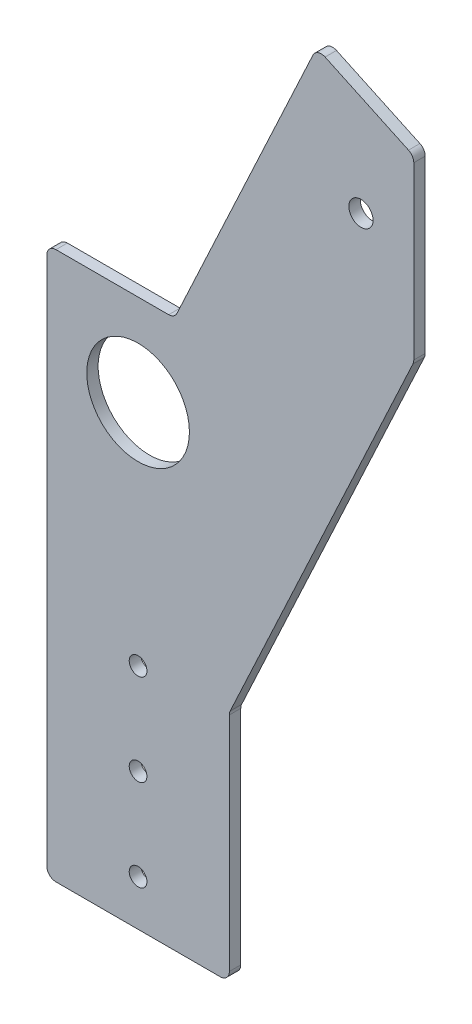
SolidWorks part; units mm, degrees
ref_plane "Front Plane" through (0, 0, 0) normal (0, 0, 1) x (1, 0, 0)
ref_plane "Top Plane" through (0, 0, 0) normal (0, 1, 0) x (1, 0, 0)
ref_plane "Right Plane" through (0, 0, 0) normal (1, 0, 0) x (0, 0, -1)
sketch "Sketch1" plane through (0, 0, 0) normal (0, 0, 1) x (1, 0, 0)
  line L0 (10.1326, 114.3) -> (49.7415, 199.2415)
  line L1 (-25.4, -38.1) -> (25.4, -38.1)
  line L2 (-25.4, 38.1) -> (-25.4, -38.1)
  line L3 (-25.4, 38.1) -> (25.4, 38.1) construction
  line L4 (25.4, -38.1) -> (25.4, 38.1)
  line L5 (-25.4, -38.1) -> (25.4, 38.1) construction
  line L6 (-25.4, 38.1) -> (25.4, -38.1) construction
  line L7 (-25.4, 38.1) -> (20.6404, 16.631) construction
  line L8 (49.7415, 199.2415) -> (95.782, 177.7725)
  line L9 (20.6404, 16.631) -> (25.4, 26.8379) construction
  line L10 (25.4, 26.8379) -> (95.782, 177.7725)
  line L11 (-25.4, 38.1) -> (-25.4, 114.3)
  line L12 (-25.4, 114.3) -> (10.1326, 114.3)
  line L13 (10.1326, 114.3) -> (-25.4, 38.1) construction
  point P0 (0, 0)
  dimension "D1" = 50.8
  dimension "D2" = 76.2
  dimension "D3" = 50.8
  dimension "D4" = 65
  dimension "D5" = 177.8
  dimension "D6" = 76.2
extrude "Boss-Extrude1" add sketch "Sketch1" along normal blind 3.175
sketch "Sketch2" plane through (0, 0, 3.175) normal (0, 0, 1) x (1, 0, 0)
  line L0 (72.7617, 188.507) -> (60.6016, 162.4294) construction
  line L1 (49.7415, 199.2415) -> (95.782, 177.7725) construction
  line L2 (60.6016, 162.4294) -> (-25.4, -22.0015) construction
  line L4 (-25.4, -38.1) -> (-25.4, 114.3) construction
  circle A0 centre (62.0272, 165.4868) radius 3.3734
  dimension "D1" = 6.7469
  dimension "D2" = 25.4
  dimension "D3" = 90
extrude "Cut-Extrude1" cut sketch "Sketch2" against normal blind 3.175
sketch "Sketch3" plane through (0, 0, 3.175) normal (0, 0, 1) x (1, 0, 0)
  line L0 (0, -38.1) -> (0, 92.5705) construction
  line L1 (-25.4, -38.1) -> (25.4, -38.1) construction
  line L2 (10.1326, 114.3) -> (49.7415, 199.2415) construction
  circle A0 centre (0, -25.4) radius 2.4638
  circle A1 centre (0, 0) radius 2.4638
  circle A2 centre (0, 25.4) radius 2.4638
  dimension "D2" = 4.9276
  dimension "D4" = 12.7
  dimension "D5" = 25.4
  dimension "D6" = 25.4
extrude "Cut-Extrude2" cut sketch "Sketch3" against normal blind 3.175
sketch "Sketch4" plane through (0, 0, 3.175) normal (0, 0, 1) x (1, 0, 0)
  circle A0 centre (0, 88.9) radius 14.2875
  dimension "D1" = 28.575
extrude "Cut-Extrude3" cut sketch "Sketch4" against normal blind 3.175
sketch "Sketch5" plane through (0, 0, 3.175) normal (0, 0, 1) x (1, 0, 0)
  line L0 (76.732, 186.6557) -> (76.732, 136.9197)
  line L1 (49.7415, 199.2415) -> (95.782, 177.7725) construction
  line L2 (25.4, 26.8379) -> (95.782, 177.7725) construction
  line L3 (76.732, 136.9197) -> (95.782, 177.7725)
  line L4 (95.782, 177.7725) -> (76.732, 186.6557)
  dimension "D1" = 19.05
extrude "Cut-Extrude4" cut sketch "Sketch5" against normal through all
fillet "Fillet1" radius 2.54 8 edges at (10.1326, 114.3, 1.5875) (-25.4, 114.3, 1.5875) (-25.4, -38.1, 1.5875) (25.4, -38.1, 1.5875) (25.4, 26.8379, 1.5875) (76.732, 136.9197, 1.5875) (76.732, 186.6557, 1.5875) (49.7415, 199.2415, 1.5875)
